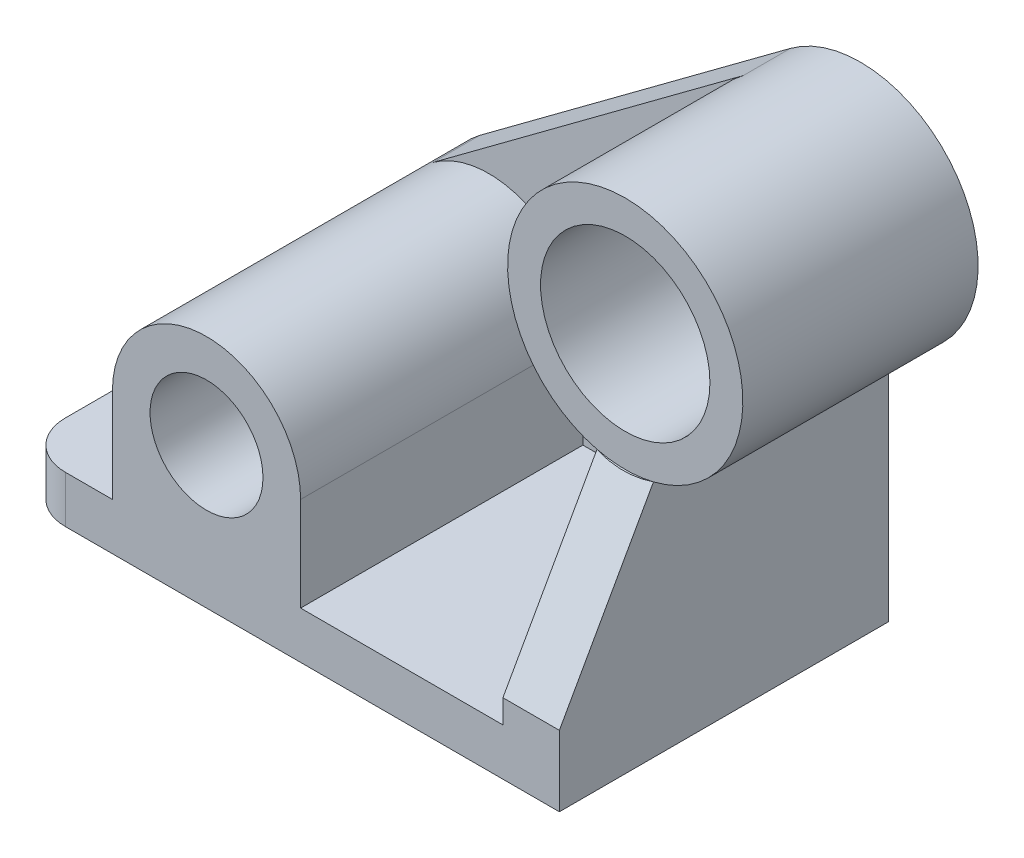
SolidWorks part; units mm, degrees
ref_plane "Front Plane" through (0, 0, 0) normal (0, 0, 1) x (1, 0, 0)
ref_plane "Top Plane" through (0, 0, 0) normal (0, 1, 0) x (1, 0, 0)
ref_plane "Right Plane" through (0, 0, 0) normal (1, 0, 0) x (0, 0, -1)
sketch "Sketch2" plane through (0, 0, 0) normal (0, 0, 1) x (1, 0, 0)
  line L0 (47.0532, -26.4242) -> (-27.9468, -26.4242)
  line L1 (47.0532, -26.4242) -> (47.0532, -16.4242)
  line L2 (47.0532, -16.4242) -> (47.0532, 24.3065)
  line L3 (-7.9468, 3.5758) -> (-7.9468, -16.4242)
  line L4 (-47.9468, 3.5758) -> (-47.9468, -16.4242)
  line L5 (-7.9468, -16.4242) -> (47.0532, -16.4242)
  line L6 (-27.9468, -26.4242) -> (-67.9468, -26.4242)
  line L7 (-67.9468, -26.4242) -> (-67.9468, -16.4242)
  line L8 (-67.9468, -16.4242) -> (-47.9468, -16.4242)
  line L9 (35.0532, -16.4242) -> (35.0532, 24.3065)
  circle A1 centre (-27.9468, 3.5758) radius 12
  arc A2 (-7.9468, 3.5758) -> (-47.9468, 3.5758) centre (-27.9468, 3.5758) ccw
  circle A3 centre (41.0532, 48.5758) radius 25
  circle A4 centre (41.0532, 48.5758) radius 18
  point P10 (47.0532, 48.5758)
  point P13 (35.0532, 48.5758)
extrude "Boss-Extrude2" add sketch "Sketch2" along normal mid plane 70 contours L3 A2 L4 L8 L7 L6 L0 L1 L5 A1 | A1 | A4 | A3 L9 L5 L2
sketch "Sketch3" plane through (0, 0, -35) normal (0, 0, 1) x (1, 0, 0)
  line L0 (26.1507, 68.6486) -> (-39.8688, 19.634)
  line L9 (-7.9468, -16.4242) -> (-7.9468, 3.5758)
  line L10 (-47.9468, 3.5758) -> (-47.9468, -16.4242)
  line L11 (-47.9468, -16.4242) -> (-67.9468, -16.4242)
  line L12 (-67.9468, -16.4242) -> (-67.9468, -26.4242)
  line L13 (-67.9468, -26.4242) -> (47.0532, -26.4242)
  line L14 (47.0532, -26.4242) -> (47.0532, 24.3065)
  line L15 (35.0532, 24.3065) -> (35.0532, -16.4242)
  line L16 (35.0532, -16.4242) -> (-7.9468, -16.4242)
  line L17 (-7.9468, -16.4242) -> (-7.9468, 3.5758)
  line L18 (-47.9468, 3.5758) -> (-47.9468, -16.4242)
  line L19 (-47.9468, -16.4242) -> (-67.9468, -16.4242)
  line L20 (-67.9468, -16.4242) -> (-67.9468, -26.4242)
  line L21 (-67.9468, -26.4242) -> (47.0532, -26.4242)
  line L22 (47.0532, -26.4242) -> (47.0532, 24.3065)
  line L23 (35.0532, 24.3065) -> (35.0532, -16.4242)
  line L24 (35.0532, -16.4242) -> (-7.9468, -16.4242)
  line L25 (-7.9468, -16.4242) -> (-7.9468, 3.5758)
  line L26 (35.0532, -16.4242) -> (-7.9468, -16.4242)
  line L27 (35.0532, 24.3065) -> (35.0532, -16.4242)
  line L28 (47.0532, -26.4242) -> (47.0532, 24.3065)
  line L29 (-67.9468, -26.4242) -> (47.0532, -26.4242)
  line L30 (-67.9468, -16.4242) -> (-67.9468, -26.4242)
  line L31 (-47.9468, -16.4242) -> (-67.9468, -16.4242)
  line L32 (-47.9468, 3.5758) -> (-47.9468, -16.4242)
  line L33 (-7.9468, -16.4242) -> (-7.9468, 3.5758)
  line L34 (35.0532, -16.4242) -> (-7.9468, -16.4242)
  line L35 (35.0532, 24.3065) -> (35.0532, -16.4242)
  line L36 (47.0532, -26.4242) -> (47.0532, 24.3065)
  line L37 (-67.9468, -26.4242) -> (47.0532, -26.4242)
  line L38 (-67.9468, -16.4242) -> (-67.9468, -26.4242)
  line L39 (-47.9468, -16.4242) -> (-67.9468, -16.4242)
  line L40 (-47.9468, 3.5758) -> (-47.9468, -16.4242)
  arc A2 (-7.9468, 3.5758) -> (-47.9468, 3.5758) centre (-27.9468, 3.5758) ccw construction
  arc A3 (47.0532, 24.3065) -> (35.0532, 24.3065) centre (41.0532, 48.5758) ccw
  arc A4 (-7.9468, 3.5758) -> (-47.9468, 3.5758) centre (-27.9468, 3.5758) ccw
  arc A5 (47.0532, 24.3065) -> (35.0532, 24.3065) centre (41.0532, 48.5758) ccw
  arc A7 (47.0532, 24.3065) -> (35.0532, 24.3065) centre (41.0532, 48.5758) ccw
  arc A8 (-7.9468, 3.5758) -> (-47.9468, 3.5758) centre (-27.9468, 3.5758) ccw
  arc A9 (47.0532, 24.3065) -> (35.0532, 24.3065) centre (41.0532, 48.5758) ccw
  arc A10 (-7.9468, 3.5758) -> (-47.9468, 3.5758) centre (-27.9468, 3.5758) ccw
  line M40 (-7.9468, 3.5758) -> (-7.9468, -16.4242)
  line M41 (-7.9468, -16.4242) -> (35.0532, -16.4242)
  line M42 (35.0532, -16.4242) -> (35.0532, 24.3065)
  arc M43 (35.0532, 24.3065) -> (47.0532, 24.3065) centre (41.0532, 48.5758) cw
  arc M49 (-47.9468, 3.5758) -> (-7.9468, 3.5758) centre (-27.9468, 3.5758) cw
  dimension "D1" = 0
  dimension "D2" = 0
extrude "Boss-Extrude5" add sketch "Sketch3" along normal blind 10 contours L0 M43 M42 M41 M40 M49
fillet "Fillet2" radius 10 1 edges at (-67.9468, -21.4242, 35)
sketch "Sketch4" plane through (0, 0, 35) normal (0, 0, 1) x (1, 0, 0)
  line L8 (-47.9468, -16.4242) -> (-57.9468, -16.4242)
  line L9 (-57.9468, -16.4242) -> (-57.9468, -26.4242)
  line L10 (-57.9468, -26.4242) -> (47.0532, -26.4242)
  line L11 (47.0532, -26.4242) -> (47.0532, 24.3065)
  line L12 (35.0532, 24.3065) -> (35.0532, -16.4242)
  line L13 (35.0532, -16.4242) -> (-7.9468, -16.4242)
  line L14 (-7.9468, -16.4242) -> (-7.9468, 3.5758)
  line L15 (-47.9468, 3.5758) -> (-47.9468, -16.4242)
  line L16 (-47.9468, -16.4242) -> (-57.9468, -16.4242)
  line L17 (-57.9468, -16.4242) -> (-57.9468, -26.4242)
  line L18 (-57.9468, -26.4242) -> (47.0532, -26.4242)
  line L19 (47.0532, -26.4242) -> (47.0532, 24.3065)
  line L20 (35.0532, 24.3065) -> (35.0532, -16.4242)
  line L21 (35.0532, -16.4242) -> (-7.9468, -16.4242)
  line L22 (-7.9468, -16.4242) -> (-7.9468, 3.5758)
  line L23 (-47.9468, 3.5758) -> (-47.9468, -16.4242)
  circle A0 centre (41.0532, 48.5758) radius 25
  arc A2 (47.0532, 24.3065) -> (35.0532, 24.3065) centre (41.0532, 48.5758) ccw
  arc A3 (-7.9468, 3.5758) -> (-47.9468, 3.5758) centre (-27.9468, 3.5758) ccw
  arc A4 (47.0532, 24.3065) -> (35.0532, 24.3065) centre (41.0532, 48.5758) ccw
  arc A5 (-7.9468, 3.5758) -> (-47.9468, 3.5758) centre (-27.9468, 3.5758) ccw
  arc M15 (47.0532, 24.3065) -> (35.0532, 24.3065) centre (41.0532, 48.5758) ccw
  circle M22 centre (41.0532, 48.5758) radius 18
  dimension "D1" = 0
extrude "Cut-Extrude1" cut sketch "Sketch4" against normal blind 20 contours A0 M15 M22
sketch "Sketch5" plane through (47.0532, 0, 0) normal (1, 0, 0) x (0, 0, -1)
  line L0 (-35, -26.4242) -> (-35, -11.4242)
  line L1 (-35, -26.4242) -> (-35, 24.3065) construction
  line L2 (-35, -11.4242) -> (-15, 24.3065)
  line L3 (-15, 24.3065) -> (-35, 24.3065)
  line L4 (-35, 24.3065) -> (-35, -11.4242)
  line M3 (-15, 24.3065) -> (-35, 24.3065)
  line M4 (-35, 24.3065) -> (-35, -26.4242)
  dimension "D1" = 15
extrude "Cut-Extrude4" cut sketch "Sketch5" against normal blind 20 contours L2 M4 M3
